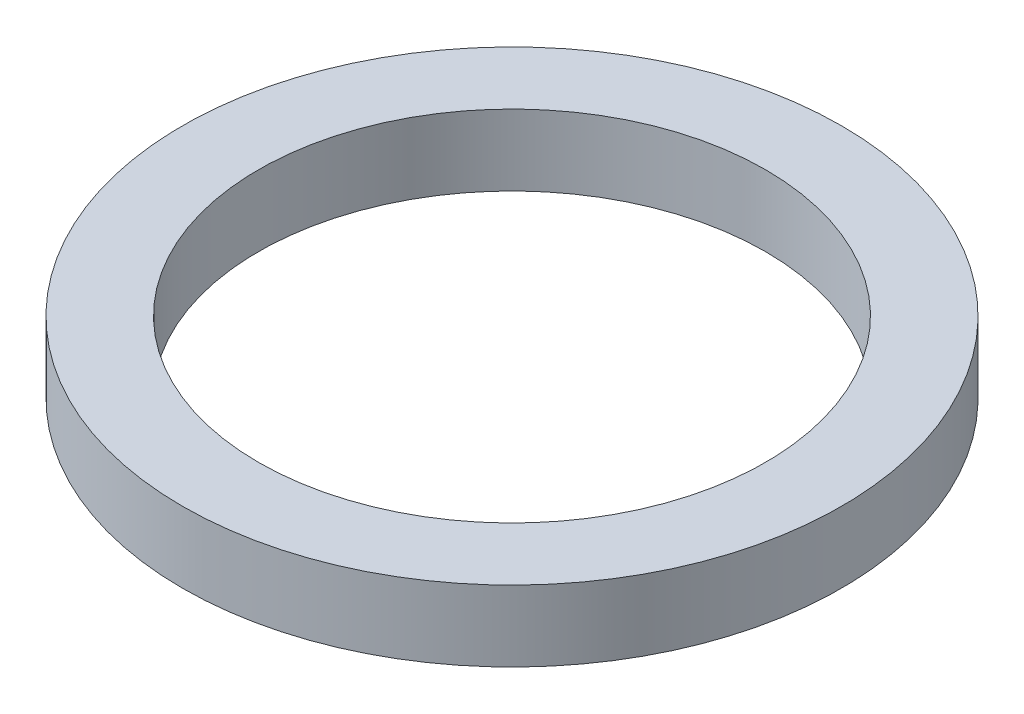
SolidWorks part; units mm, degrees
ref_plane "前视基准面" through (0, 0, 0) normal (0, 0, 1) x (1, 0, 0)
ref_plane "上视基准面" through (0, 0, 0) normal (0, 1, 0) x (1, 0, 0)
ref_plane "右视基准面" through (0, 0, 0) normal (1, 0, 0) x (0, 0, -1)
other "Configuration Table"
sketch "草图1" plane through (0, 0, 0) normal (0, 1, 0) x (1, 0, 0)
  circle A0 centre (0, 0) radius 32.5
  circle A1 centre (0, 0) radius 25
  dimension "D1" = 65
  dimension "D2" = 50
extrude "凸台-拉伸1" add sketch "草图1" along normal blind 7
